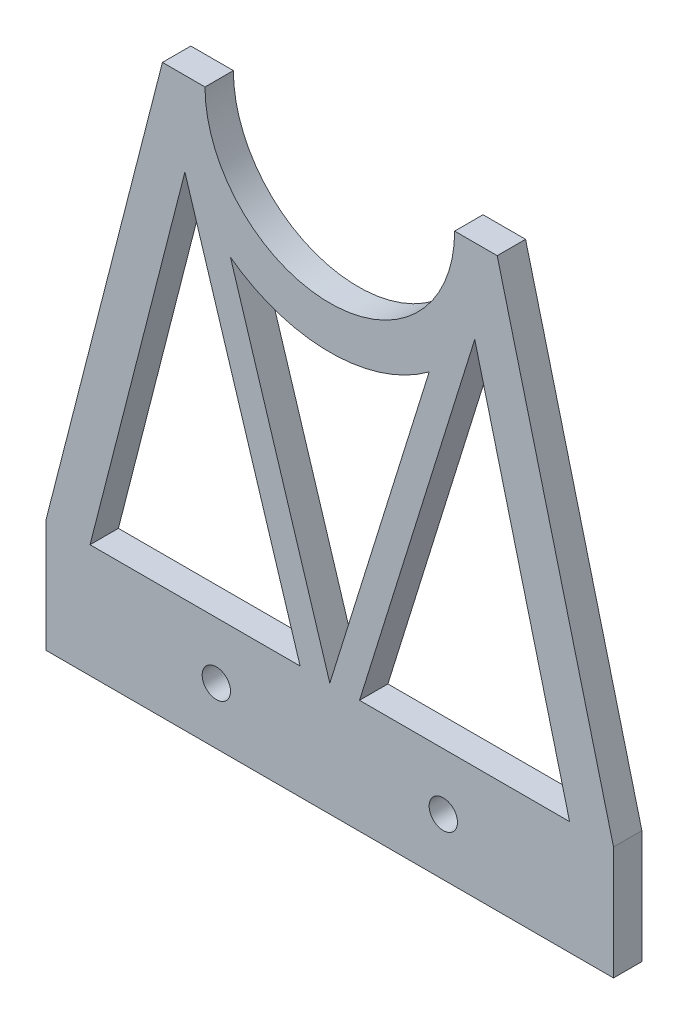
SolidWorks part; units mm, degrees
ref_plane "Front Plane" through (0, 0, 0) normal (0, 0, 1) x (1, 0, 0)
ref_plane "Top Plane" through (0, 0, 0) normal (0, 1, 0) x (1, 0, 0)
ref_plane "Right Plane" through (0, 0, 0) normal (1, 0, 0) x (0, 0, -1)
sketch "Sketch1" plane through (0, 0, 0) normal (0, 0, 1) x (1, 0, 0)
  line L0 (-27.94, 70.104) -> (-37.465, 70.104)
  line L1 (-106.1335, 70.104) -> (-27.94, 70.104) construction
  line L2 (-106.1335, 70.104) -> (-106.1335, -56.896) construction
  line L3 (-106.1335, -56.896) -> (97.0665, -56.896) construction
  line L4 (97.0665, 70.104) -> (97.0665, -56.896) construction
  line L5 (27.94, 70.104) -> (37.465, 70.104)
  line L6 (-63.5, -56.896) -> (63.5, -56.896)
  line L7 (63.5, -56.896) -> (63.5, -31.496)
  line L8 (27.94, 70.104) -> (97.0665, 70.104) construction
  line L9 (53.6672, -31.496) -> (6.6504, -31.496)
  line L10 (-63.5, -31.496) -> (-63.5, -56.896)
  line L11 (0, -151.6178) -> (0, 60.8153) construction
  line L12 (-37.465, 70.104) -> (-63.5, -31.496)
  line L13 (37.465, 70.104) -> (63.5, -31.496)
  line L14 (32.4365, 51.3557) -> (53.6672, -31.496)
  line L15 (-32.4365, 51.3557) -> (-53.6672, -31.496)
  line L16 (-28.2381, 67.7396) -> (-54.2731, -33.8604) construction
  line L17 (28.2381, 67.7396) -> (54.2731, -33.8604) construction
  line L18 (0, -31.496) -> (22.2368, 39.9519)
  line L19 (6.6504, -31.496) -> (28.3, 38.0649)
  line L20 (28.3, 38.0649) -> (32.4365, 51.3557)
  line L21 (-28.3, 38.0649) -> (-32.4365, 51.3557)
  line L22 (-6.6504, -31.496) -> (-28.3, 38.0649)
  line L23 (0, -31.496) -> (-22.2368, 39.9519)
  line L24 (-6.6504, -31.496) -> (-53.6672, -31.496)
  arc A0 (-27.94, 70.104) -> (27.94, 70.104) centre (0, 70.104) ccw
  arc A1 (-22.2368, 39.9519) -> (22.2368, 39.9519) centre (0, 70.104) ccw
  point P0 (0, 0)
  point P21 (0, -56.896)
  point P33 (0, 0)
  point P35 (32.8573, 52.1032)
  dimension "D1" = 127
  dimension "D2" = 203.2
  dimension "D11" = 25.4
  dimension "D12" = 127
  dimension "D14" = 9.525
extrude "Boss-Extrude1" add sketch "Sketch1" along normal blind 6.35
sketch "Sketch2" plane through (0, 0, 6.35) normal (0, 0, 1) x (1, 0, 0)
  line L0 (-101.6, -56.896) -> (101.6, -56.896) construction
  line L1 (-101.6, 70.104) -> (-101.6, -56.896) construction
  line L2 (101.6, -56.896) -> (101.6, 70.104) construction
  circle A0 centre (-25.4, -44.196) radius 3.175
  circle A1 centre (25.4, -44.196) radius 3.175
  dimension "D1" = 12.7
  dimension "D2" = 12.7
  dimension "D3" = 6.35
  dimension "D4" = 76.2
  dimension "D5" = 76.2
extrude "Cut-Extrude1" cut sketch "Sketch2" against normal blind 18.415
